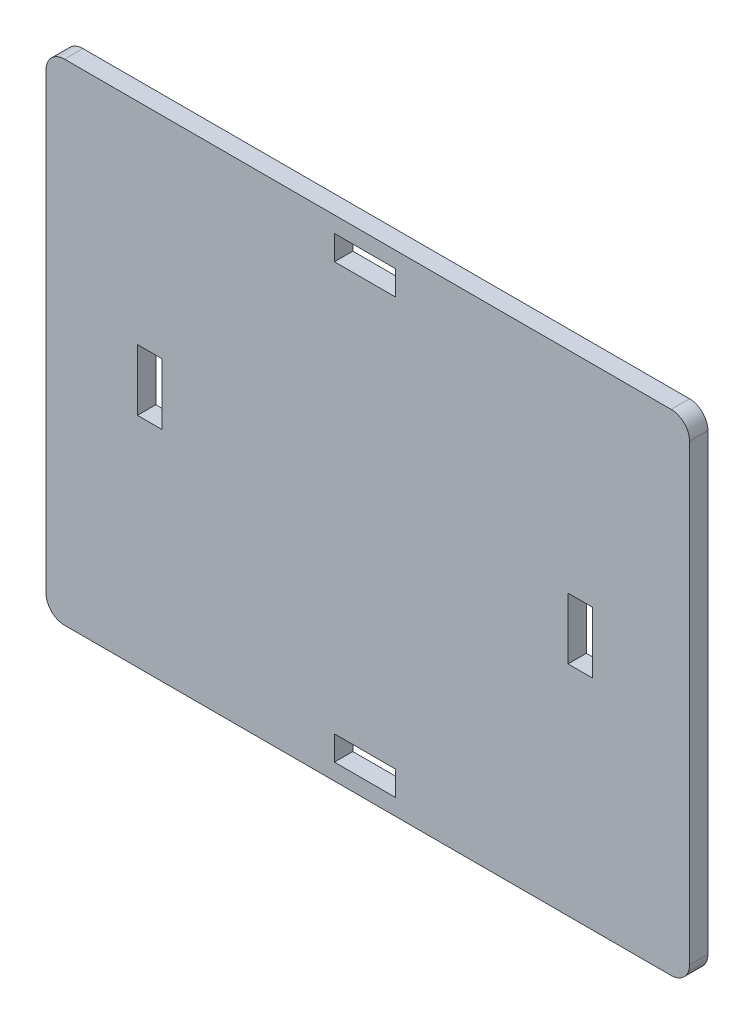
SolidWorks part; units mm, degrees
ref_plane "Front Plane" through (0, 0, 0) normal (0, 0, 1) x (1, 0, 0)
ref_plane "Top Plane" through (0, 0, 0) normal (0, 1, 0) x (1, 0, 0)
ref_plane "Right Plane" through (0, 0, 0) normal (1, 0, 0) x (0, 0, -1)
sketch "Sketch1" plane through (0, 0, 0) normal (0, 0, 1) x (1, 0, 0)
  line L1 (52.5, -40) -> (-52.5, -40)
  line L2 (52.5, -40) -> (52.5, 40)
  line L3 (52.5, 40) -> (-52.5, 40)
  line L4 (-52.5, -40) -> (-52.5, 40)
  line L5 (52.5, -40) -> (-52.5, 40) construction
  line L6 (52.5, 40) -> (-52.5, -40) construction
  point P0 (0, 0)
  dimension "D1" = 80
  dimension "D2" = 105
extrude "Boss-Extrude1" add sketch "Sketch1" along normal blind 3
sketch "Sketch3" plane through (0, 0, 0) normal (0, 0, -1) x (-1, 0, 0)
  circle A0 centre (-24.5095, 24.5095) radius 3.75
  circle A1 centre (24.5095, 24.5095) radius 3.75
  circle A2 centre (24.5095, -24.5095) radius 3.75
  circle A3 centre (-24.5095, -24.5095) radius 3.75
  dimension "D1" = 7.5
  dimension "D2" = 7.5
  dimension "D3" = 7.5
  dimension "D4" = 7.5
extrude "Cut-Extrude1" cut sketch "Sketch3" against normal blind 2.2
sketch "Sketch4" plane through (0, 0, 3) normal (0, 0, 1) x (1, 0, 0)
  line L1 (4.5537, 37.3891) -> (-5.4463, 37.3891)
  line L2 (4.5537, 37.3891) -> (4.5537, 33.3891)
  line L3 (4.5537, 33.3891) -> (-5.4463, 33.3891)
  line L4 (-5.4463, 37.3891) -> (-5.4463, 33.3891)
  line L5 (4.5537, 37.3891) -> (-5.4463, 33.3891) construction
  line L6 (4.5537, 33.3891) -> (-5.4463, 37.3891) construction
  line L7 (-5.4463, -33.3245) -> (4.5537, -33.3245)
  line L8 (-5.4463, -33.3245) -> (-5.4463, -37.3245)
  line L9 (-5.4463, -37.3245) -> (4.5537, -37.3245)
  line L10 (4.5537, -33.3245) -> (4.5537, -37.3245)
  line L11 (-5.4463, -33.3245) -> (4.5537, -37.3245) construction
  line L12 (-5.4463, -37.3245) -> (4.5537, -33.3245) construction
  line L13 (-33.5868, 5.6177) -> (-37.5868, 5.6177)
  line L14 (-33.5868, 5.6177) -> (-33.5868, -4.3823)
  line L15 (-33.5868, -4.3823) -> (-37.5868, -4.3823)
  line L16 (-37.5868, 5.6177) -> (-37.5868, -4.3823)
  line L17 (-33.5868, 5.6177) -> (-37.5868, -4.3823) construction
  line L18 (-33.5868, -4.3823) -> (-37.5868, 5.6177) construction
  line L19 (36.6693, -4.3823) -> (32.6693, -4.3823)
  line L20 (36.6693, -4.3823) -> (36.6693, 5.6177)
  line L21 (36.6693, 5.6177) -> (32.6693, 5.6177)
  line L22 (32.6693, -4.3823) -> (32.6693, 5.6177)
  line L23 (36.6693, -4.3823) -> (32.6693, 5.6177) construction
  line L24 (36.6693, 5.6177) -> (32.6693, -4.3823) construction
  point P0 (-0.4463, 35.3891)
  point P5 (-0.4463, -35.3245)
  point P10 (-35.5868, 0.6177)
  point P15 (34.6693, 0.6177)
  dimension "D1" = 10
  dimension "D2" = 4
  dimension "D3" = 10
  dimension "D4" = 4
  dimension "D5" = 10
  dimension "D6" = 4
  dimension "D7" = 10
  dimension "D8" = 4
extrude "Cut-Extrude2" cut sketch "Sketch4" against normal blind 10
fillet "Fillet2" radius 3 1 edges at (-52.5, -40, 1.5)
fillet "Fillet3" radius 3 3 edges at (-52.5, 40, 1.5) (52.5, 40, 1.5) (52.5, -40, 1.5)
